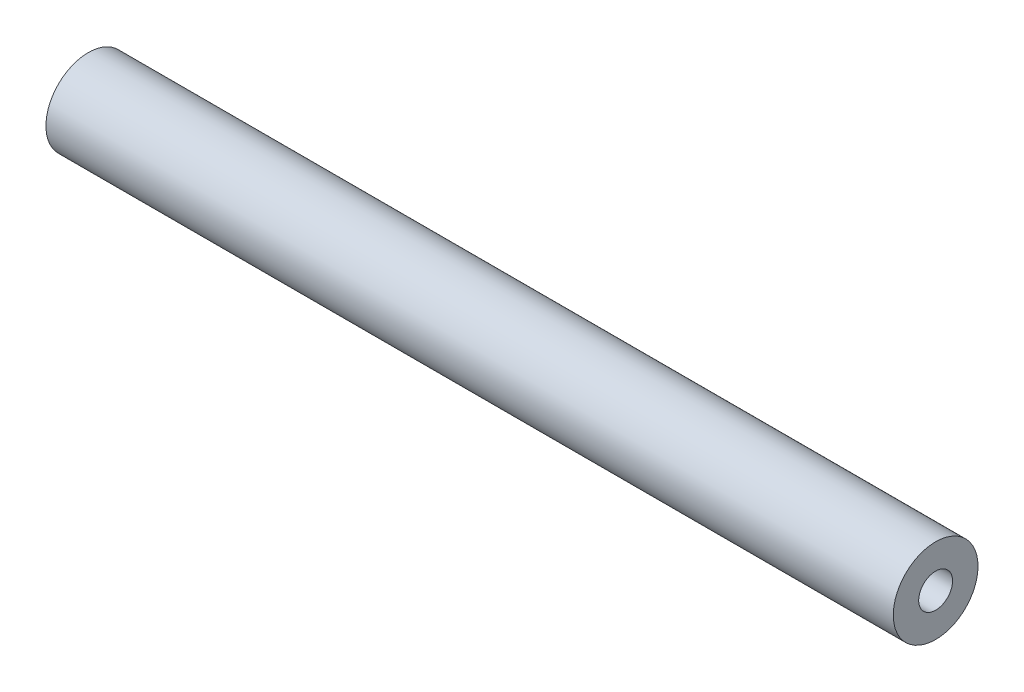
SolidWorks part; units mm, degrees
ref_plane "前视基准面" through (0, 0, 0) normal (0, 0, 1) x (1, 0, 0)
ref_plane "上视基准面" through (0, 0, 0) normal (0, 1, 0) x (1, 0, 0)
ref_plane "右视基准面" through (0, 0, 0) normal (1, 0, 0) x (0, 0, -1)
sketch "草图1" plane through (0, 0, 0) normal (1, 0, 0) x (0, 0, -1)
  circle A0 centre (0, 0) radius 2
  circle A1 centre (0, 0) radius 5
  dimension "D1" = 4
  dimension "D2" = 10
extrude "凸台-拉伸1" add sketch "草图1" along normal mid plane 100
